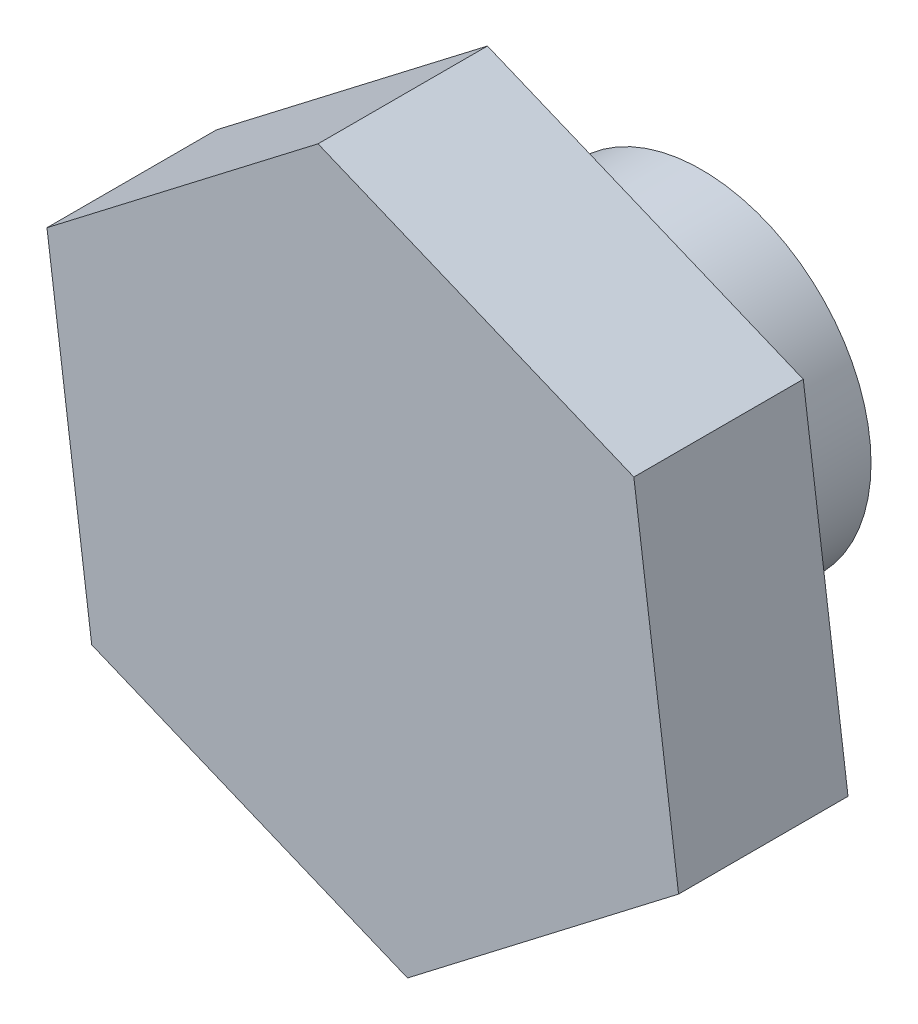
SolidWorks part; units mm, degrees
ref_plane "Plan de face" through (0, 0, 0) normal (1, 0, 0) x (0, 1, 0)
ref_plane "Plan de dessus" through (0, 0, 0) normal (0, 0, 1) x (0, 1, 0)
ref_plane "Plan de droite" through (0, 0, 0) normal (0, 1, 0) x (-1, 0, 0)
sketch "Esquisse1" plane through (0, 0, 0) normal (0, 0, 1) x (0, 1, 0)
  line L1 (19.282, 46.6025) -> (-30.718, 40)
  line L2 (-30.718, 40) -> (-50, -6.6025)
  line L3 (-50, -6.6025) -> (-19.282, -46.6025)
  line L4 (-19.282, -46.6025) -> (30.718, -40)
  line L5 (30.718, -40) -> (50, 6.6025)
  line L6 (50, 6.6025) -> (19.282, 46.6025)
  circle A0 centre (0, 0) radius 43.6772 construction
  dimension "D1" = 50
  dimension "D2" = 40
extrude "Boss.-Extru.1" add sketch "Esquisse1" along normal blind 25
sketch "Esquisse2" plane through (0, 0, 0) normal (0, 0, 1) x (0, 1, 0)
  circle A0 centre (0, 0) radius 25
  circle A1 centre (0, 0) radius 12.5
  dimension "D1" = 50
extrude "Boss.-Extru.2" add sketch "Esquisse2" against normal blind 25
